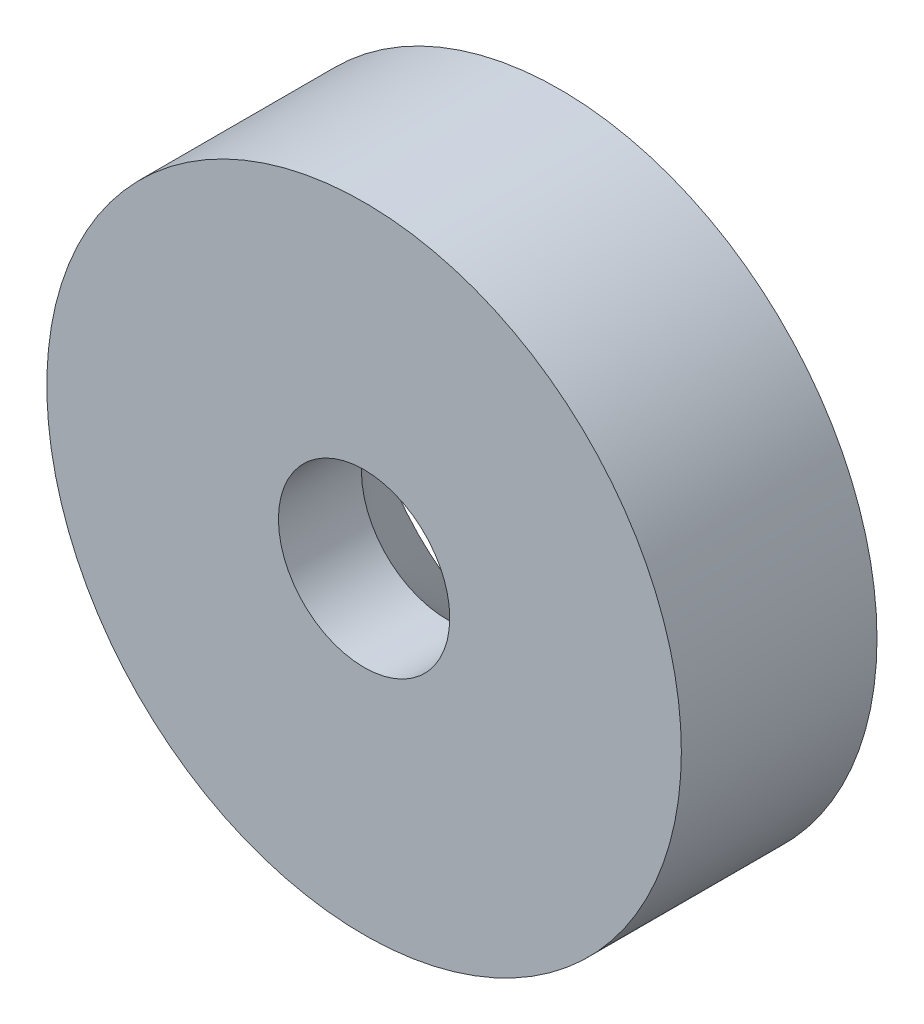
SolidWorks part; units mm, degrees
ref_plane "Front Plane" through (0, 0, 0) normal (0, 0, 1) x (1, 0, 0)
ref_plane "Top Plane" through (0, 0, 0) normal (0, 1, 0) x (1, 0, 0)
ref_plane "Right Plane" through (0, 0, 0) normal (1, 0, 0) x (0, 0, -1)
sketch "Sketch1" plane through (0, 0, 0) normal (0, 0, 1) x (1, 0, 0)
  circle A0 centre (5.0563, 23.079) radius 6
  circle A1 centre (5.0563, 23.079) radius 1.62
extrude "Boss-Extrude1" add sketch "Sketch1" along normal blind 3.7
sketch "Sketch2" plane through (0, 0, 0) normal (0, 0, -1) x (-1, 0, 0)
  circle A0 centre (-5.0563, 23.079) radius 3.75
  dimension "D1" = 7.5
extrude "Cut-Extrude1" cut sketch "Sketch2" against normal blind 10 draft 45
